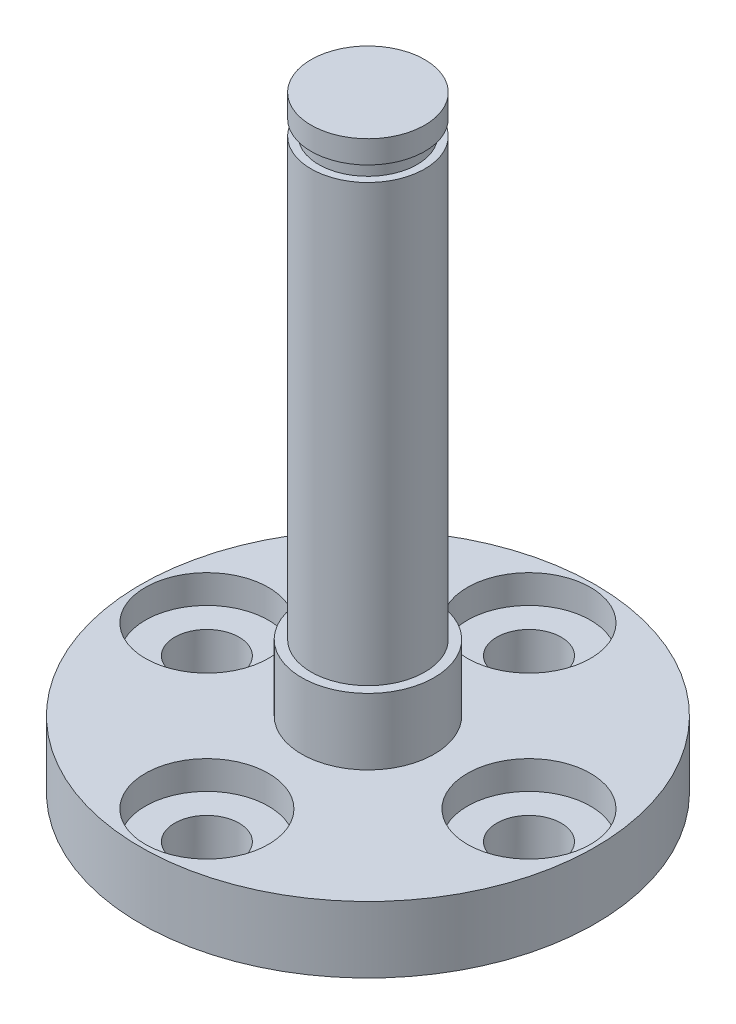
SolidWorks part; units mm, degrees
material "45"
ref_plane "前视基准面" through (0, 0, 0) normal (0, 0, 1) x (1, 0, 0)
ref_plane "上视基准面" through (0, 0, 0) normal (0, 1, 0) x (1, 0, 0)
ref_plane "右视基准面" through (0, 0, 0) normal (1, 0, 0) x (0, 0, -1)
sketch "草图1" plane through (0, 0, 0) normal (0, 0, 1) x (1, 0, 0)
  line L0 (0, 0) -> (0, 67.0401) construction
  line L1 (3, 27.3) -> (3, 28.5)
  line L2 (3, 27.3) -> (2.6, 27.3)
  line L3 (0, 0) -> (3.5, 0)
  line L4 (3.5, 0) -> (3.5, 3.5)
  line L5 (3.5, 3.5) -> (3, 3.5)
  line L8 (3, 3.5) -> (3, 26.5)
  line L9 (3, 28.5) -> (0, 28.5)
  line L10 (0, 28.5) -> (0, 0)
  line L12 (3, 26.5) -> (2.6, 26.5)
  line L13 (2.6, 27.3) -> (2.6, 26.5)
  dimension "D1" = 3
  dimension "D2" = 28.5
  dimension "D3" = 3.5
  dimension "D4" = 1.2
  dimension "D5" = 0.8
  dimension "D6" = 3.5
  dimension "D9" = 0.4
revolve "旋转1" add sketch "草图1" angle 360 about L0
sketch "草图2" plane through (0, 0, 0) normal (0, -1, 0) x (1, 0, 0)
  circle A0 centre (0, 0) radius 12
extrude "凸台-拉伸1" add sketch "草图2" along normal blind 3.5
sketch "草图3" plane through (0, -3.5, 0) normal (0, -1, 0) x (1, 0, 0)
  circle A0 centre (0, 0) radius 2.95
  dimension "D1" = 5.9
extrude "凸台-拉伸2" add sketch "草图3" along normal blind 2
hole_wizard "M3 六角凹头螺钉的柱形沉头孔1" positions "草图5" profile "草图4" counterbore size "M3" standard "Iso" end condition through all
sketch "草图5" plane through (0, 0, 0) normal (0, 1, 0) x (1, 0, 0)
  point P0 (8.5, 0)
  dimension "D1" = 8.5
sketch "草图4" plane through (8.5, 0, 0) normal (1, 0, 0) x (0, 0, 1)
  line L0 (0, 0) -> (0, 5.5)
  line L1 (0, 5.5) -> (1.7, 5.5)
  line L3 (1.7, 5.5) -> (1.7, 1.5)
  line L4 (1.7, 1.5) -> (3.25, 1.5)
  line L5 (3.25, 1.5) -> (3.25, 0)
  line L7 (3.25, 0) -> (0, 0)
  line L11 (0, -6.35) -> (0, 107.95) construction
  dimension "通孔孔直径" = 3.4
  dimension "通孔孔深度" = 5.5
  dimension "柱形沉头孔直径" = 6.5
  dimension "柱形沉头孔深度" = 1.5
pattern_circular "阵列(圆周)1" count 4 over 360 about axis through (0, 0, 0) along (0, 1, 0) of "M3 六角凹头螺钉的柱形沉头孔1"
